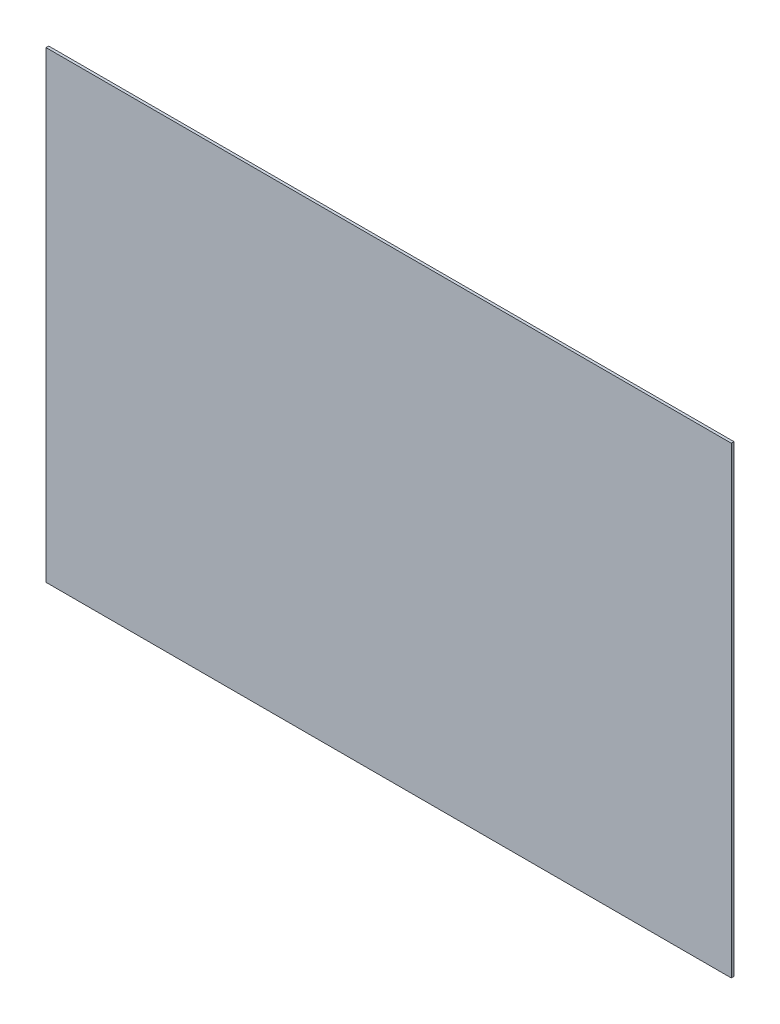
SolidWorks part; units mm, degrees
ref_plane "Top Plane" through (0, 0, 0) normal (0, 0, 1) x (1, 0, 0)
ref_plane "Right Plane" through (0, 0, 0) normal (0, 1, 0) x (1, 0, 0)
ref_plane "Front Plane" through (0, 0, 0) normal (1, 0, 0) x (0, 0, -1)
sketch "Sketch1" plane through (0, 0, 0) normal (0, 0, 1) x (1, 0, 0)
  line L1 (-127.25, 86) -> (127.25, 86)
  line L2 (-127.25, 86) -> (-127.25, -86)
  line L3 (-127.25, -86) -> (127.25, -86)
  line L4 (127.25, 86) -> (127.25, -86)
  line L5 (-127.25, 86) -> (127.25, -86) construction
  line L6 (-127.25, -86) -> (127.25, 86) construction
  point P4 (0, 0)
  point P5 (0, 0)
  dimension "D1" = 254.5
  dimension "D2" = 172
extrude "Boss-Extrude1" add sketch "Sketch1" along normal blind 1
sketch "Sketch2" plane through (0, 0, 0) normal (0, 0, -1) x (-1, 0, 0)
  line L0 (0, 71.5) -> (0, -76.5) construction
  line L1 (115, -76.5) -> (-115, -76.5)
  line L2 (115, -76.5) -> (115, 71.5)
  line L3 (115, 71.5) -> (-115, 71.5)
  line L4 (-115, -76.5) -> (-115, 71.5)
  line L5 (-127.25, 86) -> (127.25, 86) construction
  point P4 (0, 0)
  point P5 (0, 0)
  point P9 (2.2206, -71.3944)
  dimension "D1" = 230
  dimension "D2" = 148
  dimension "D3" = 14.5
extrude "Boss-Extrude2" add sketch "Sketch2" along normal blind 9
sketch "Sketch3" plane through (0, 0, -9) normal (0, 0, -1) x (-1, 0, 0)
  line L0 (115, 71.5) -> (-115, 71.5) construction
  line L1 (29, -26.5) -> (-29, -26.5) construction
  line L2 (29, -26.5) -> (29, 22.5) construction
  line L3 (29, 22.5) -> (-29, 22.5) construction
  line L4 (-29, -26.5) -> (-29, 22.5) construction
  line L5 (29, -26.5) -> (-29, 22.5) construction
  line L6 (29, 22.5) -> (-29, -26.5) construction
  line L7 (0, -2) -> (0, 0) construction
  circle A0 centre (29, -26.5) radius 1.75
  circle A1 centre (-29, -26.5) radius 1.75
  circle A2 centre (-29, 22.5) radius 1.75
  circle A3 centre (29, 22.5) radius 1.75
  point P4 (0, -2)
  dimension "D4" = 3.5
  dimension "D1" = 49
  dimension "D2" = 49
  dimension "D3" = 58
extrude "Cut-Extrude1" cut sketch "Sketch3" against normal blind 2
